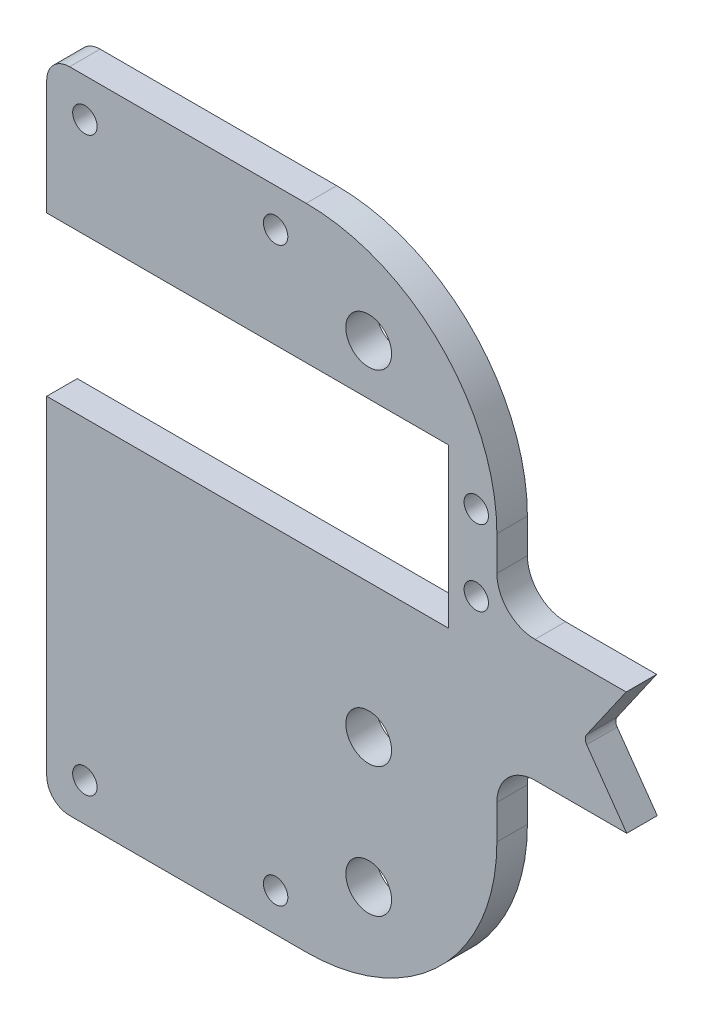
SolidWorks part; units mm, degrees
ref_plane "正面" through (0, 0, 0) normal (0, 0, 1) x (1, 0, 0)
ref_plane "平面" through (0, 0, 0) normal (0, 1, 0) x (1, 0, 0)
ref_plane "右側面" through (0, 0, 0) normal (1, 0, 0) x (0, 0, -1)
sketch "ｽｹｯﾁ1" plane through (0, 0, 0) normal (0, 0, 1) x (1, 0, 0)
  line L0 (-32, -28) -> (-32, 51) construction
  line L1 (-32, -31) -> (27, -31)
  line L2 (-32, -31) -> (-32, 54)
  line L3 (-32, 54) -> (27, 54)
  line L4 (27, -31) -> (27, 54)
  line L5 (2, -31) -> (-29, -31) construction
  line L6 (-29, 54) -> (2, 54) construction
  line L7 (27, 54) -> (27, -31) construction
  line L11 (-32, -10.4) -> (-32, 10.4)
  line L14 (-32, 15.1) -> (20.65, 15.1)
  line L15 (-32, 15.1) -> (-32, 35.9)
  line L16 (-32, 35.9) -> (20.65, 35.9)
  line L17 (20.65, 15.1) -> (20.65, 35.9)
  line L20 (-20, 35.75) -> (20, 35.75) construction
  line L21 (20, 15.25) -> (-20, 15.25) construction
  line L22 (20.5, 34.75) -> (20.5, 16.25) construction
  circle A4 centre (24.3, 30.45) radius 1.6
  circle A5 centre (24.3, 20.55) radius 1.6
  circle A8 centre (10.2, -19.5) radius 3
  circle A9 centre (10.2, 42.5) radius 3
  circle A10 centre (10.2, -19.5) radius 3 construction
  circle A20 centre (10.2, 42.5) radius 2.7 construction
  circle A21 centre (10.2, -19.5) radius 2 construction
  dimension "D6" = 3.2
  dimension "D1" = 0
  dimension "D2" = 0
  dimension "D3" = 0
  dimension "D4" = 0
  dimension "D9" = 0.15
  dimension "D10" = 0.15
  dimension "D11" = 0.15
extrude "ﾎﾞｽ - 押し出し1" add sketch "ｽｹｯﾁ1" along normal blind 4
fillet "ﾌｨﾚｯﾄ1" radius 3 2 edges at (-32, 54, 2) (-32, -31, 2)
fillet "ﾌｨﾚｯﾄ2" radius 25 2 edges at (27, 54, 2) (27, -31, 2)
sketch "ｽｹｯﾁ2" plane through (0, 0, 0) normal (0, 0, -1) x (-1, 0, 0)
  circle A0 centre (27, 49) radius 1.6
  circle A1 centre (27, -26) radius 1.6
  dimension "D1" = 3.2
extrude "ｶｯﾄ - 押し出し1" cut sketch "ｽｹｯﾁ2" against normal blind 10
sketch "ｽｹｯﾁ3" plane through (0, 0, 0) normal (0, 0, -1) x (-1, 0, 0)
  circle A0 centre (-10.2, -2.5) radius 3
  dimension "D1" = 6
extrude "ｶｯﾄ - 押し出し2" cut sketch "ｽｹｯﾁ3" against normal blind 10
sketch "ｽｹｯﾁ4" plane through (0, 0, 0) normal (0, 0, -1) x (-1, 0, 0)
  line L0 (-27, 19.5) -> (-43.9453, 19.5)
  line L1 (-43.9453, 19.5) -> (-38.3642, 11.5)
  line L2 (-38.3642, 11.5) -> (-44.0236, 3.5)
  line L3 (-44.0236, 3.5) -> (-27, 3.5)
  line L4 (-27, 3.5) -> (-27, 19.5)
  line L5 (-27, -6) -> (-27, 29) construction
  line L6 (-27, 11.5) -> (-45.68, 11.5) construction
  line L7 (-38.3642, 11.5) -> (-27, 11.5) construction
  line L8 (-40.7591, 14.933) -> (-27, 14.933) construction
  circle A0 centre (-45.68, 11.5) radius 6 construction
  point P8 (-40.7591, 14.933)
  point P12 (-27, 11.5)
  point P18 (-41.136, 7.5819)
  dimension "D3" = 18.68
  dimension "D4" = 5
  dimension "D6" = 13.7591
  dimension "D5" = 12
  dimension "D1" = 0
  dimension "D2" = 16
extrude "ﾎﾞｽ - 押し出し2" add sketch "ｽｹｯﾁ4" against normal blind 4
fillet "ﾌｨﾚｯﾄ3" radius 5 2 edges at (27, 19.5, 2) (27, 3.5, 2)
fillet "ﾌｨﾚｯﾄ4" radius 1 1 edges at (38.3642, 11.5, 2)
sketch "ｽｹｯﾁ5" plane through (0, 0, 4) normal (0, 0, 1) x (1, 0, 0)
  circle A0 centre (-2, -26) radius 1.6
  circle A1 centre (-2, 49) radius 1.6
  circle A2 centre (-27, -26) radius 1.6 construction
extrude "ｶｯﾄ - 押し出し3" cut sketch "ｽｹｯﾁ5" against normal blind 10
